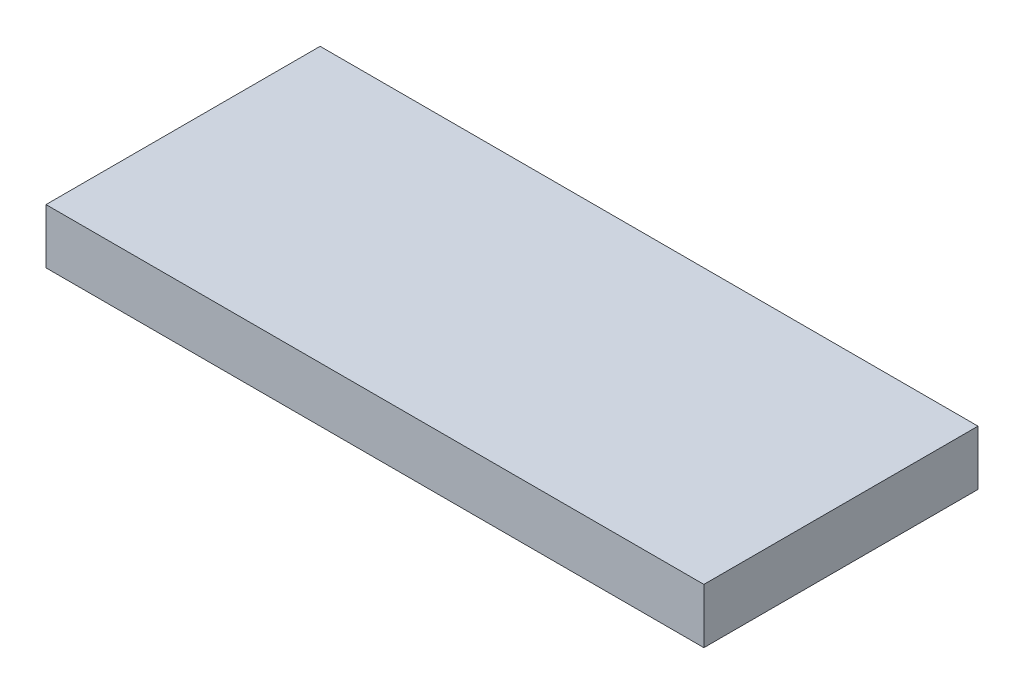
SolidWorks part; units mm, degrees
ref_plane "Front Plane" through (0, 0, 0) normal (0, 0, 1) x (1, 0, 0)
ref_plane "Top Plane" through (0, 0, 0) normal (0, 1, 0) x (1, 0, 0)
ref_plane "Right Plane" through (0, 0, 0) normal (1, 0, 0) x (0, 0, -1)
sketch "Sketch1" plane through (0, 0, 0) normal (0, 1, 0) x (1, 0, 0)
  line L1 (-375.7574, 304.7576) -> (824.2426, 304.7576)
  line L2 (-375.7574, 304.7576) -> (-375.7574, -195.2424)
  line L3 (-375.7574, -195.2424) -> (824.2426, -195.2424)
  line L4 (824.2426, 304.7576) -> (824.2426, -195.2424)
extrude "Boss-Extrude1" add sketch "Sketch1" along normal blind 100
